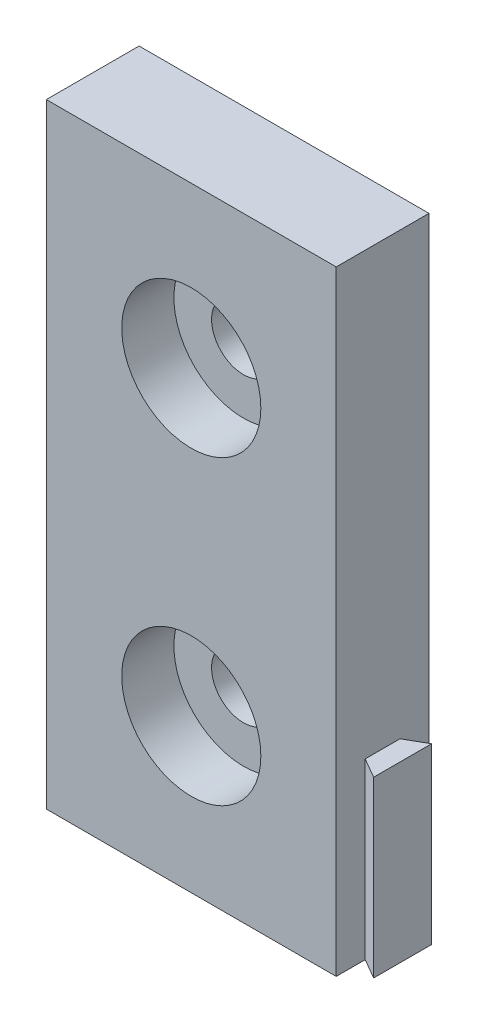
SolidWorks part; units mm, degrees
ref_plane "Front Plane" through (0, 0, 0) normal (0, 0, 1) x (1, 0, 0)
ref_plane "Top Plane" through (0, 0, 0) normal (0, 1, 0) x (1, 0, 0)
ref_plane "Right Plane" through (0, 0, 0) normal (1, 0, 0) x (0, 0, -1)
sketch "Sketch2" plane through (0, 0, 0) normal (0, 0, 1) x (1, 0, 0)
  line L0 (12.5, 53) -> (12.5, -45.5968) construction
  line L1 (0, 0) -> (25, 0)
  line L2 (0, 0) -> (0, 53)
  line L3 (0, 53) -> (25, 53)
  line L4 (25, 0) -> (25, 53)
  line L5 (0, 26.2) -> (42.3407, 26.2) construction
  circle A0 centre (12.5, 39.2) radius 2.75
  circle A1 centre (12.5, 13.2) radius 2.75
  dimension "D3" = 5.5
  dimension "D4" = 13
  dimension "D1" = 53
  dimension "D2" = 25
  dimension "D5" = 13
  dimension "D6" = 26.2
extrude "Boss-Extrude1" add sketch "Sketch2" along normal blind 8
sketch "Sketch3" plane through (0, 0, 0) normal (0, -1, 0) x (1, 0, 0)
  line L0 (25, 2.5) -> (26.7321, 1.5)
  line L1 (26.7321, 1.5) -> (26.7321, 6.5)
  line L2 (26.7321, 6.5) -> (25, 5.5)
  line L3 (25, 8) -> (25, 0) construction
  line L4 (25, 2.5) -> (25, 5.5)
  point P6 (25, 1.2778)
  point P7 (25, 9.7239)
  point P8 (25, 1.2126)
  point P9 (28.7311, -0.5412)
  point P10 (25, -1.8086)
  point P11 (25, 4)
  point P12 (25, 4)
  point P13 (28.8393, 0.5026)
  point P14 (27.7097, 5.0605)
  dimension "D1" = 60
  dimension "D2" = 60
  dimension "D3" = 5
  dimension "D4" = 3
extrude "Boss-Extrude2" add sketch "Sketch3" against normal blind 15
sketch "Sketch4" plane through (0, 0, 8) normal (0, 0, 1) x (1, 0, 0)
  circle A0 centre (12.5, 39.2) radius 6
  circle A1 centre (12.5, 13.2) radius 6
  dimension "D1" = 12
extrude "Cut-Extrude1" cut sketch "Sketch4" against normal blind 4.5
